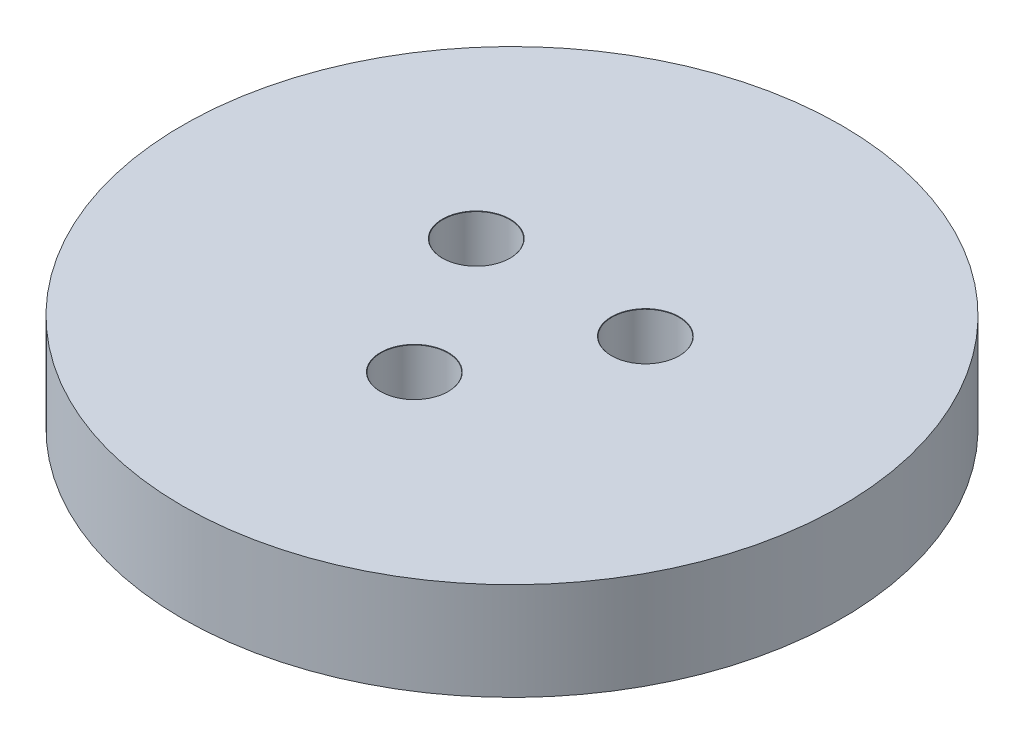
SolidWorks part; units mm, degrees
ref_plane "Front Plane" through (0, 0, 0) normal (0, 0, 1) x (1, 0, 0)
ref_plane "Top Plane" through (0, 0, 0) normal (0, 1, 0) x (1, 0, 0)
ref_plane "Right Plane" through (0, 0, 0) normal (1, 0, 0) x (0, 0, -1)
sketch "Sketch1" plane through (0, 0, 0) normal (0, 1, 0) x (1, 0, 0)
  circle A0 centre (0, 0) radius 27
  dimension "D1" = 54
extrude "Boss-Extrude1" add sketch "Sketch1" along normal blind 8
sketch "Sketch5" plane through (0, 8, 0) normal (0, 1, 0) x (1, 0, 0)
  line L0 (-6.9282, 4) -> (0, 0) construction
  line L1 (0, 0) -> (6.9282, 4) construction
  line L3 (0, 0) -> (0, -8) construction
  point P0 (-6.9282, 4)
  point P2 (6.9282, 4)
  point P4 (0, -8)
  dimension "D1" = 8
  dimension "D2" = 120
  dimension "D3" = 120
hole_wizard "M5 Clearance Hole1" positions "Sketch5" profile "Sketch4" hole size "M5" standard "ANSI Metric" end condition through all
sketch "Sketch4" plane through (-6.9282, 8, -4) normal (1, 0, 0) x (0, 0, 1)
  line L0 (0, 0) -> (0, 8)
  line L1 (0, 8) -> (2.75, 8)
  line L2 (2.75, 8) -> (2.75, 0.025)
  line L3 (2.75, 0.025) -> (2.775, 0)
  line L5 (2.775, 0) -> (0, 0)
  line L6 (-2.75, 0.025) -> (-2.775, 0) construction
  line L11 (0, -6.35) -> (0, 107.95) construction
  dimension "Thru Hole Dia." = 5.5
  dimension "Thru Hole Depth" = 8
  dimension "Near C'Sink Dia." = 5.55
  dimension "Near C'Sink Angle" = 90
